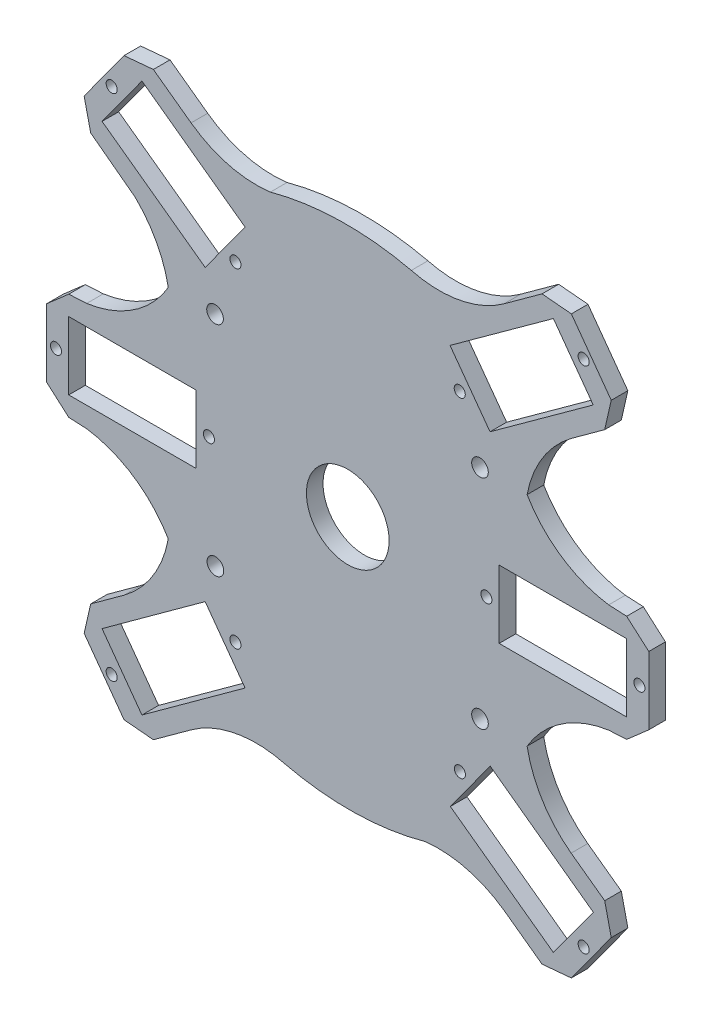
SolidWorks part; units mm, degrees
ref_plane "Front Plane" through (0, 0, 0) normal (0, 0, 1) x (1, 0, 0)
ref_plane "Top Plane" through (0, 0, 0) normal (0, 1, 0) x (1, 0, 0)
ref_plane "Right Plane" through (0, 0, 0) normal (1, 0, 0) x (0, 0, -1)
sketch "Sketch1" plane through (0, 0, 0) normal (0, 0, 1) x (1, 0, 0)
  line L0 (82.6471, 154.5675) -> (89.8444, 164.4737)
  line L1 (89.8444, 164.4737) -> (95.1377, 164.9541)
  line L2 (95.1377, 164.9541) -> (101.9432, 160.0096)
  line L3 (82.6471, 154.5675) -> (83.8259, 149.3848)
  line L4 (83.8259, 149.3848) -> (91.8556, 143.3481)
  line L5 (79.8696, 122.2086) -> (83.1031, 122.3792)
  line L6 (79.8696, 122.2086) -> (75.8696, 118.7086)
  line L7 (75.8696, 118.7086) -> (75.8696, 106.4639)
  line L8 (75.8696, 106.4639) -> (79.8696, 102.9639)
  line L9 (79.8696, 102.9639) -> (83.1033, 102.7933)
  line L10 (89.8837, 80.1889) -> (83.8259, 75.7877)
  line L11 (83.8259, 75.7877) -> (82.6471, 70.605)
  line L12 (82.6471, 70.605) -> (89.8444, 60.6988)
  line L13 (89.8444, 60.6988) -> (95.1377, 60.2183)
  line L14 (95.1377, 60.2183) -> (101.9432, 65.1628)
  line L15 (158.4561, 65.1629) -> (165.2616, 60.2184)
  line L16 (165.2616, 60.2184) -> (170.5549, 60.6988)
  line L17 (170.5549, 60.6988) -> (177.7522, 70.605)
  line L18 (177.7522, 70.605) -> (176.5734, 75.7877)
  line L19 (176.5734, 75.7877) -> (170.5156, 80.1889)
  line L20 (177.2961, 102.7933) -> (180.5296, 102.9639)
  line L21 (180.5296, 102.9639) -> (184.5296, 106.4639)
  line L22 (184.5296, 106.4639) -> (184.5296, 118.7087)
  line L23 (184.5296, 118.7087) -> (180.5296, 122.2087)
  line L24 (180.5296, 122.2087) -> (177.296, 122.3793)
  line L25 (170.5156, 144.9836) -> (176.5734, 149.3848)
  line L26 (176.5734, 149.3848) -> (177.7522, 154.5675)
  line L27 (177.7522, 154.5675) -> (170.5549, 164.4737)
  line L28 (170.5549, 164.4737) -> (165.2616, 164.9541)
  line L29 (165.2616, 164.9541) -> (158.4561, 160.0096)
  arc A0 (91.8556, 143.3481) -> (97.8316, 132.2338) centre (77.3868, 128.4048) cw
  arc A1 (97.8316, 132.2338) -> (83.1031, 122.3792) centre (80.2598, 142.5624) cw
  arc A2 (83.1033, 102.7933) -> (97.8316, 92.9386) centre (80.2368, 82.5757) cw
  arc A3 (97.8316, 92.9386) -> (89.8837, 80.1889) centre (77.6246, 96.683) cw
  arc A4 (101.9432, 65.1628) -> (118.7213, 68.3416) centre (113.6989, 48.9825) cw
  arc A5 (158.4561, 65.1629) -> (144.1476, 68.8189) centre (146.5546, 48.412) ccw
  arc A6 (118.7213, 68.3416) -> (144.1476, 68.8189) centre (130.508, 117.9337) ccw
  arc A7 (170.5156, 80.1889) -> (162.5677, 92.9387) centre (182.7781, 96.6852) cw
  arc A8 (177.2961, 102.7933) -> (162.5677, 92.9387) centre (180.261, 82.4285) ccw
  arc A9 (177.296, 122.3793) -> (162.5677, 132.2339) centre (180.1625, 142.5969) cw
  arc A10 (170.5156, 144.9836) -> (162.5677, 132.2339) centre (182.9461, 128.3825) ccw
  arc A11 (101.9432, 160.0096) -> (116.2517, 156.3536) centre (113.6989, 176.19) ccw
  arc A12 (158.4561, 160.0096) -> (141.678, 156.8309) centre (146.7004, 176.19) cw
  arc A13 (116.2517, 156.3536) -> (141.678, 156.8309) centre (129.9159, 105.9281) cw
extrude "Boss-Extrude1" add sketch "Sketch1" along normal blind 3 contours A13 A12 L29 L28 L27 L26 L25 A10 A9 L24 L23 L22 L21 L20 A8 A7 L19 L18 L17 L16 L15 A5 A6 A4 L14 L13 L12 L11 L10 A3 A2 L9 L8 L7 L6 L5 A1 A0 L4 L3 L0 L1 L2 A11
sketch "Sketch2" plane through (0, 0, 3) normal (0, 0, 1) x (1, 0, 0)
  line L2 (85.8832, 152.2164) -> (93.0777, 162.1187)
  line L3 (85.8832, 152.2164) -> (104.4906, 138.6973)
  line L4 (104.4906, 138.6973) -> (111.6851, 148.5997)
  line L5 (111.6851, 148.5997) -> (93.0777, 162.1187)
  line L6 (111.6846, 76.5742) -> (104.4897, 86.4763)
  line L7 (79.8696, 118.7086) -> (79.8696, 106.4686)
  line L8 (79.8696, 106.4686) -> (102.8696, 106.4686)
  line L9 (102.8696, 106.4686) -> (102.8696, 118.7086)
  line L10 (79.8696, 118.7086) -> (102.8696, 118.7086)
  line L11 (85.8831, 72.9562) -> (93.0777, 63.0545)
  line L12 (93.0777, 63.0545) -> (111.6846, 76.5742)
  line L13 (104.4897, 86.4763) -> (85.8831, 72.9562)
  line L14 (167.3188, 162.1226) -> (174.5028, 152.2126)
  line L15 (174.5028, 152.2126) -> (155.8812, 138.7132)
  line L16 (167.3188, 162.1226) -> (148.6647, 148.5997)
  line L17 (148.6647, 148.5997) -> (155.8812, 138.7132)
  line L18 (180.5296, 118.7086) -> (180.5296, 106.4686)
  line L19 (180.5296, 106.4686) -> (157.5296, 106.4686)
  line L20 (157.5296, 106.4686) -> (157.5296, 118.7086)
  line L21 (157.5296, 118.7086) -> (180.5296, 118.7086)
  line L22 (174.5161, 72.9561) -> (167.3173, 63.0569)
  line L23 (167.3173, 63.0569) -> (148.7158, 76.5842)
  line L24 (148.7158, 76.5842) -> (155.9147, 86.4834)
  line L25 (155.9147, 86.4834) -> (174.5161, 72.9561)
extrude "Cut-Extrude1" cut sketch "Sketch2" against normal blind 3
sketch "Sketch3" plane through (0, 0, 3) normal (0, 0, 1) x (1, 0, 0)
  circle A2 centre (130.2119, 112.5662) radius 7.46
  circle A3 centre (87.6197, 158.5195) radius 1
  circle A4 centre (109.9486, 142.2966) radius 1
  circle A5 centre (172.773, 158.5175) radius 1
  circle A6 centre (150.4152, 142.3004) radius 1
  circle A7 centre (182.8296, 112.5886) radius 1
  circle A8 centre (155.2296, 112.5886) radius 1
  circle A9 centre (105.1696, 112.5886) radius 1
  circle A10 centre (77.5676, 112.5886) radius 1
  circle A11 centre (109.9478, 82.8773) radius 1
  circle A12 centre (87.6197, 66.6534) radius 1
  circle A13 centre (172.7768, 66.6538) radius 1
  circle A14 centre (150.4551, 82.8865) radius 1
extrude "Cut-Extrude2" cut sketch "Sketch3" against normal blind 3
sketch "Sketch4" plane through (0, 0, 3) normal (0, 0, 1) x (1, 0, 0)
  circle A0 centre (106.2677, 132.2977) radius 1.5
  circle A1 centre (154.0677, 132.2339) radius 1.5
  circle A2 centre (106.3316, 92.9386) radius 1.5
  circle A3 centre (154.0677, 92.9387) radius 1.5
extrude "Cut-Extrude4" cut sketch "Sketch4" against normal blind 3
